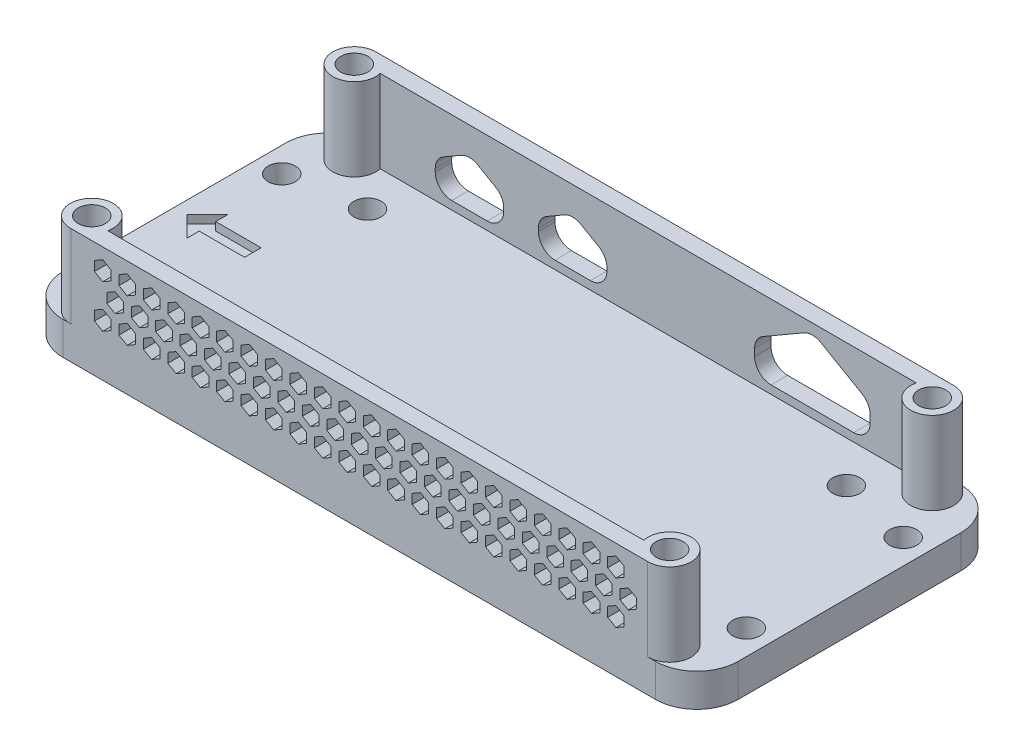
SolidWorks part; units mm, degrees
ref_plane "Płaszczyzna przednia" through (0, 0, 0) normal (0, 0, 1) x (1, 0, 0)
ref_plane "Płaszczyzna górna" through (0, 0, 0) normal (0, 1, 0) x (1, 0, 0)
ref_plane "Płaszczyzna prawa" through (0, 0, 0) normal (1, 0, 0) x (0, 0, -1)
sketch "Szkic1" plane through (0, 0, 0) normal (0, 1, 0) x (1, 0, 0)
  line L0 (-40.885, 0) -> (-37.885, 0) construction
  line L1 (-40.885, -18.5) -> (40.885, -18.5)
  line L2 (-40.885, -18.5) -> (-40.885, 18.5)
  line L3 (-40.885, 18.5) -> (40.885, 18.5)
  line L4 (40.885, -18.5) -> (40.885, 18.5)
  line L5 (-40.885, -18.5) -> (40.885, 18.5) construction
  line L6 (-40.885, 18.5) -> (40.885, -18.5) construction
  line L7 (-37.885, 0) -> (-37.885, 10) construction
  line L8 (-55, 0) -> (55, 0) construction
  line L10 (40.885, 0) -> (37.885, 0) construction
  line L11 (37.885, 0) -> (37.885, 9.5) construction
  circle A2 centre (-37.885, 10) radius 1.65
  circle A3 centre (-37.885, -10) radius 1.65
  circle A6 centre (37.885, 9.5) radius 1.65
  circle A7 centre (37.885, -9.5) radius 1.65
  point P0 (0, 0)
  dimension "D1" = 10
  dimension "D2" = 3.3
  dimension "D6" = 3.3
  dimension "D3" = 3
  dimension "D4" = 37
  dimension "D5" = 75.77
  dimension "D7" = 9.5
extrude "Dodanie-wyciągnięcie1" add sketch "Szkic1" along normal blind 4
fillet "Zaokrąglenie1" radius 5 4 edges at (-40.885, 2, -18.5) (40.885, 2, -18.5) (40.885, 2, 18.5) (-40.885, 2, 18.5)
sketch "Szkic2" plane through (0, 4, 0) normal (0, 1, 0) x (1, 0, 0)
  line L0 (-36.235, 10) -> (36.235, 10) construction
  line L1 (36.235, 9.5) -> (36.235, 10) construction
  line L2 (0, 10) -> (0, 0) construction
  line L4 (-29, 11.5) -> (29, 11.5) construction
  line L5 (-29, 11.5) -> (-29, -11.5) construction
  line L6 (-29, -11.5) -> (29, -11.5) construction
  line L7 (29, 11.5) -> (29, -11.5) construction
  line L8 (-29, 11.5) -> (29, -11.5) construction
  line L9 (-29, -11.5) -> (29, 11.5) construction
  circle A0 centre (-37.885, 10) radius 1.65 construction
  circle A1 centre (29, 11.5) radius 1.65
  circle A2 centre (37.885, 9.5) radius 1.65 construction
  circle A3 centre (29, -11.5) radius 1.65
  circle A4 centre (-29, -11.5) radius 1.65
  circle A5 centre (-29, 11.5) radius 1.65
  dimension "D3" = 3.3
  dimension "D4" = 3.3
  dimension "D5" = 3.3
  dimension "D6" = 3.3
  dimension "D1" = 58
  dimension "D2" = 23
extrude "Wytnij-wyciągnięcie11" cut sketch "Szkic2" against normal blind 3.5
ref_plane "Płaszczyzna2" through (0, 0, -11.5) normal (0, 0, -1) x (-1, 0, 0)
sketch "Szkic4" [suppressed] plane through (0, 0, -11.5) normal (0, 0, -1) x (-1, 0, 0)
  line L0 (-29, 4) -> (-28.7, 4) construction
  line L1 (29, 4) -> (-29, 4) construction
  line L2 (29, 4) -> (-29, 4) construction
  line L3 (-28.7, 4) -> (-28.7, 4.2)
  line L4 (-28.7, 4.2) -> (-25.7, 4.2)
  line L5 (-25.7, 4.2) -> (-27.6, 6.1)
  line L6 (-27.6, 6.1) -> (-27.6, 5.9)
  line L7 (-27.6, 5.9) -> (-27.9, 5.6)
  line L8 (-27.9, 5.6) -> (-27.9, 4)
  line L9 (-27.9, 4) -> (-28.7, 4)
  line L10 (-29, 4) -> (-29, 4.3161) construction
  dimension "D1" = 1.6
  dimension "D3" = 0.2
  dimension "D4" = 1.1
  dimension "D5" = 0.3
  dimension "D6" = 135
  dimension "D7" = 135
  dimension "D8" = 1.1
ref_plane "Płaszczyzna3" through (29, 0, 0) normal (1, 0, 0) x (0, 0, -1)
ref_plane "Płaszczyzna4" through (0, 0, 0) normal (-1, 0, 0) x (0, 0, 1)
sketch "Szkic6" plane through (0, 4, 0) normal (0, 1, 0) x (1, 0, 0)
  line L0 (-34.885, -18.5) -> (-34.885, -16.5)
  line L1 (-35.885, -18.5) -> (35.885, -18.5) construction
  line L2 (-34.885, -16.5) -> (34.885, -16.5)
  line L3 (34.885, -16.5) -> (34.885, -18.5)
  line L4 (34.885, -18.5) -> (-34.885, -18.5)
  line L5 (-40.885, 13.5) -> (-40.885, -13.5) construction
  line L6 (40.885, -13.5) -> (40.885, 13.5) construction
  dimension "D1" = 6
  dimension "D2" = 2
  dimension "D3" = 6
extrude "Dodanie-wyciągnięcie2" add sketch "Szkic6" along normal blind 10
mirror "Lustro4" about plane through (0, 0, 0) normal (0, 0, 1) of "Dodanie-wyciągnięcie2"
sketch "Szkic7" plane through (0, 0, -18.5) normal (0, 0, -1) x (-1, 0, 0)
  line L0 (0, 0) -> (5, 0) construction
  line L1 (-35.885, 0) -> (35.885, 0) construction
  line L2 (5, 0) -> (5, 5) construction
  line L3 (5, 5) -> (5, 14)
  line L4 (34.885, 14) -> (-34.885, 14) construction
  line L6 (25.8, 14) -> (25.8, 5)
  line L10 (17.5, 14) -> (25.8, 14)
  line L11 (5, 14) -> (13.3, 14)
  line L12 (13.3, 14) -> (13.3, 5)
  line L13 (13.3, 5) -> (5, 5)
  line L14 (13.3, 5) -> (17.5, 5) construction
  line L15 (17.5, 5) -> (25.8, 5)
  line L16 (17.5, 14) -> (17.5, 5)
  dimension "D1" = 5
  dimension "D2" = 5
  dimension "D3" = 8.3
  dimension "D4" = 8.3
  dimension "D5" = 4.2
extrude "Wytnij-wyciągnięcie1" cut sketch "Szkic7" against normal up to surface (2 mm away) up to face at (0, 9, -16.5)
sketch "Szkic8" plane through (0, 0, -18.5) normal (0, 0, -1) x (-1, 0, 0)
  line L0 (5, 14) -> (5, 8.5)
  line L1 (5, 14) -> (5, 5) construction
  line L2 (5, 8.5) -> (13.3, 8.5) construction
  line L3 (13.3, 5) -> (13.3, 14) construction
  line L4 (9.15, 8.5) -> (9.15, 10.896) construction
  line L5 (5, 8.5) -> (9.15, 10.896)
  line L6 (9.15, 10.896) -> (13.3, 8.5)
  line L7 (13.3, 8.5) -> (13.3, 14)
  line L8 (13.3, 14) -> (5, 14)
  line L9 (15.4, 14) -> (15.4, 5.5312) construction
  line L10 (17.5, 14) -> (13.3, 14) construction
  line L11 (21.65, 8.5) -> (21.65, 10.896) construction
  line L12 (25.8, 8.5) -> (17.5, 8.5) construction
  line L13 (17.5, 14) -> (25.8, 14)
  line L14 (17.5, 8.5) -> (17.5, 14)
  line L15 (21.65, 10.896) -> (17.5, 8.5)
  line L16 (25.8, 8.5) -> (21.65, 10.896)
  line L17 (25.8, 14) -> (25.8, 8.5)
  dimension "D1" = 30
  dimension "D2" = 5.5
extrude "Dodanie-wyciągnięcie3" add sketch "Szkic8" against normal up to surface (2 mm away) up to face at (-10.2667, 9.3333, -16.5)
fillet "Zaokrąglenie2" radius 2 10 edges at (-25.8, 5, -17.5) (-17.5, 5, -17.5) (-13.3, 5, -17.5) (-5, 5, -17.5) (-21.65, 10.896, -17.5) (-9.15, 10.896, -17.5) (-25.8, 8.5, -17.5) (-17.5, 8.5, -17.5) (-13.3, 8.5, -17.5) (-5, 8.5, -17.5)
sketch "Szkic15" plane through (0, 0, -18.5) normal (0, 0, -1) x (-1, 0, 0)
  line L0 (-34.885, 14) -> (-19.885, 14) construction
  line L1 (34.885, 14) -> (-34.885, 14) construction
  line L2 (-19.885, 14) -> (-19.885, 13.0415) construction
  line L3 (-19.885, 13.0415) -> (-12.885, 9)
  line L4 (-12.885, 9) -> (-12.885, 5)
  line L5 (-12.885, 5) -> (-26.885, 5)
  line L6 (-19.885, 13.0415) -> (-19.885, 5) construction
  line L7 (-26.885, 9) -> (-26.885, 5)
  line L8 (-19.885, 13.0415) -> (-26.885, 9)
  line L9 (-35.885, 0) -> (35.885, 0) construction
  dimension "D1" = 60
  dimension "D2" = 5
  dimension "D3" = 7
  dimension "D4" = 4
  dimension "D5" = 15
extrude "Wytnij-wyciągnięcie6" cut sketch "Szkic15" against normal up to surface (2 mm away) contours L4 L5 L7 L8 L3
sketch "Szkic11" plane through (0, 4, 0) normal (0, 1, 0) x (1, 0, 0)
  line L0 (0, 0) -> (-35, 0) construction
  line L1 (-35, 0) -> (-35, -15.9) construction
  circle A1 centre (-35, -15.9) radius 2.6
  dimension "D1" = 5.2
  dimension "D3" = 35
  dimension "D2" = 15.9
extrude "Dodanie-wyciągnięcie4" add sketch "Szkic11" along normal up to surface (10 mm away) up to face at (0, 14, 17.5)
sketch "Szkic14" plane through (0, 14, 0) normal (0, 1, 0) x (1, 0, 0)
  circle A0 centre (-35, -15.9) radius 1.65
  dimension "D1" = 3.3
extrude "Wytnij-wyciągnięcie5" cut sketch "Szkic14" against normal blind 4.2
mirror "Lustro6" about plane through (0, 0, 0) normal (0, 0, 1) of "Wytnij-wyciągnięcie5", "Dodanie-wyciągnięcie4"
mirror "Lustro7" about plane through (0, 0, 0) normal (1, 0, 0) of "Lustro6", "Dodanie-wyciągnięcie4", "Wytnij-wyciągnięcie5"
sketch "Szkic13" plane through (0, 4, 0) normal (0, 1, 0) x (1, 0, 0)
  line L0 (-40.885, 0) -> (-39.385, 0) construction
  line L1 (-40.885, 13.5) -> (-40.885, -13.5) construction
  line L2 (-39.385, 0) -> (-36.885, 2.5)
  line L3 (-36.885, 2.5) -> (-36.885, 1)
  line L4 (-36.885, 1) -> (-31.385, 1)
  line L5 (-31.385, 1) -> (-31.385, -1)
  line L6 (-36.885, -1) -> (-31.385, -1)
  line L7 (-36.885, -2.5) -> (-36.885, -1)
  line L8 (-39.385, 0) -> (-36.885, -2.5)
  point P10 (-31.385, 0)
  dimension "D1" = 5
  dimension "D2" = 45
  dimension "D3" = 2
  dimension "D4" = 8
  dimension "D5" = 1.5
extrude "Wytnij-wyciągnięcie4" cut sketch "Szkic13" against normal blind 1
fillet "Zaokrąglenie3" radius 2 5 edges at (26.885, 5, -17.5) (26.885, 9, -17.5) (19.885, 13.0415, -17.5) (12.885, 9, -17.5) (12.885, 5, -17.5)
sketch "Szkic18" plane through (0, 0, 18.5) normal (0, 0, 1) x (1, 0, 0)
  line L0 (-31.0702, 14) -> (-31.0702, 11.5) construction
  line L1 (-34.885, 14) -> (34.885, 14) construction
  line L2 (-31.0702, 11.5) -> (-30.5702, 10.634) construction
  line L3 (-31.0702, 10.3453) -> (-30.0702, 10.9226)
  line L4 (-30.0702, 10.9226) -> (-30.0702, 12.0774)
  line L5 (-30.0702, 12.0774) -> (-31.0702, 12.6547)
  line L6 (-31.0702, 12.6547) -> (-32.0702, 12.0774)
  line L7 (-32.0702, 12.0774) -> (-32.0702, 10.9226)
  line L8 (-32.0702, 10.9226) -> (-31.0702, 10.3453)
  line L9 (-30.5702, 10.634) -> (-29.5702, 8.9019) construction
  line L10 (-29.5702, 8.9019) -> (-30.0702, 8.0359) construction
  line L11 (-29.5702, 10.0566) -> (-30.5702, 9.4793)
  line L12 (-30.5702, 9.4793) -> (-30.5702, 8.3246)
  line L13 (-30.5702, 8.3246) -> (-29.5702, 7.7472)
  line L14 (-29.5702, 7.7472) -> (-28.5702, 8.3246)
  line L15 (-28.5702, 8.3246) -> (-28.5702, 9.4793)
  line L16 (-28.5702, 9.4793) -> (-29.5702, 10.0566)
  line L17 (-30.0702, 8.0359) -> (-31.0702, 6.3038) construction
  line L19 (-31.0702, 5.1491) -> (-30.0702, 5.7265)
  line L20 (-30.0702, 5.7265) -> (-30.0702, 6.8812)
  line L21 (-30.0702, 6.8812) -> (-31.0702, 7.4585)
  line L22 (-31.0702, 7.4585) -> (-32.0702, 6.8812)
  line L23 (-32.0702, 6.8812) -> (-32.0702, 5.7265)
  line L24 (-32.0702, 5.7265) -> (-31.0702, 5.1491)
  circle A0 centre (-31.0702, 11.5) radius 1 construction
  circle A1 centre (-29.5702, 8.9019) radius 1 construction
  circle A2 centre (-31.0702, 6.3038) radius 1 construction
  dimension "D1" = 2.5
  dimension "D2" = 2
  dimension "D3" = 2
  dimension "D4" = 3
  dimension "D5" = 3
  dimension "D6" = 2
  dimension "D7" = 1.4
extrude "Wytnij-wyciągnięcie9" cut sketch "Szkic18" against normal up to surface (2 mm away) up to face at (0, 9, 16.5)
pattern_linear "Szyk liniowy1" count 22 spacing 2.96 along (1, 0, 0) of "Wytnij-wyciągnięcie9"
